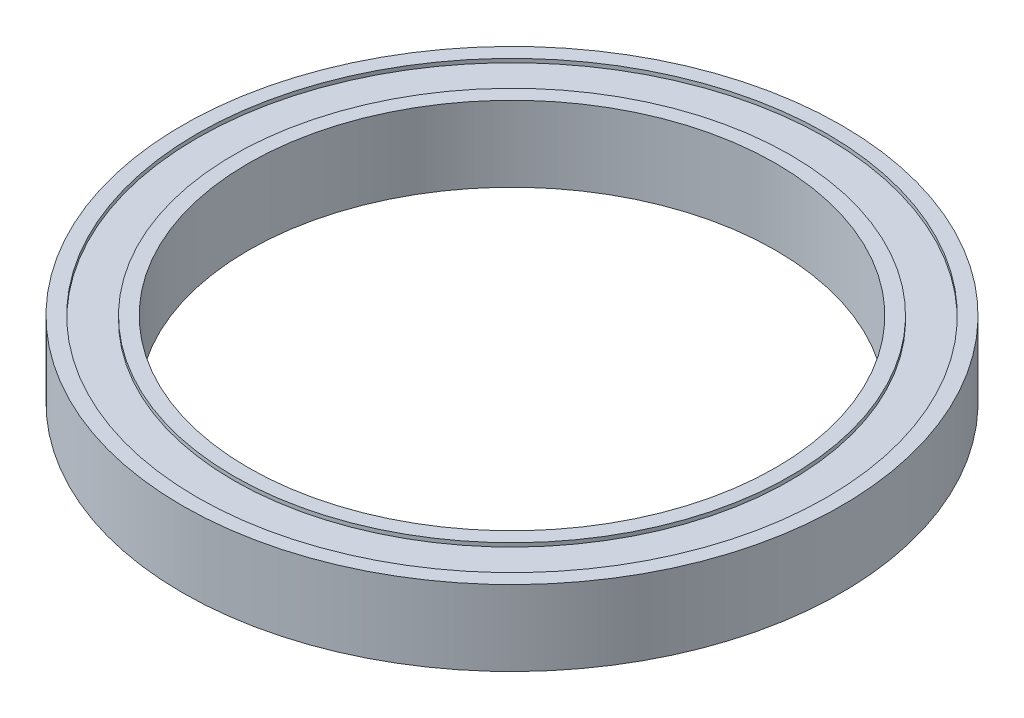
SolidWorks part; units mm, degrees
material "AISI 304"
ref_plane "前视基准面" through (0, 0, 0) normal (0, 0, 1) x (1, 0, 0)
ref_plane "上视基准面" through (0, 0, 0) normal (0, 1, 0) x (1, 0, 0)
ref_plane "右视基准面" through (0, 0, 0) normal (1, 0, 0) x (0, 0, -1)
other "Configuration Table"
sketch "草图2" plane through (0, 0, 0) normal (0, 0, 1) x (1, 0, 0)
  line L0 (0, 0) -> (0, 0.8612) construction
  line L1 (0, 0) -> (1.8966, 0) construction
  line L2 (14, 2) -> (14, -2)
  line L3 (14, 2) -> (14.7778, 2)
  line L4 (14.7778, 2) -> (14.7778, 1.8)
  line L5 (14.7778, 1.8) -> (16.7222, 1.8)
  line L6 (16.7222, 1.8) -> (16.7222, 2)
  line L7 (16.7222, 2) -> (17.5, 2)
  line L8 (17.5, 2) -> (17.5, -2)
  line L9 (16.7222, -2) -> (17.5, -2)
  line L10 (16.7222, -1.8) -> (16.7222, -2)
  line L11 (14.7778, -1.8) -> (16.7222, -1.8)
  line L12 (14.7778, -2) -> (14.7778, -1.8)
  line L13 (14, -2) -> (14.7778, -2)
  point P15 (17.5, 0)
  point P20 (14, 0)
  dimension "D1" = 4
  dimension "D2" = 28
  dimension "D3" = 35
  dimension "D4" = 0.7778
  dimension "D5" = 0.2
revolve "旋转1" add sketch "草图2" angle 360 about L0
equation "\"内径\" = 28"
equation "\"外径\" = 35"
equation "\"D1@草图2\" = \"厚\""
equation "\"D2@草图2\"=\"内径\""
equation "\"D3@草图2\"=\"外径\""
equation "\"D4@草图2\"=(\"外径\"-\"内径\")/9"
equation "\"D5@草图2\"= \"厚\" / 20"
equation "\"厚\" = 4"
